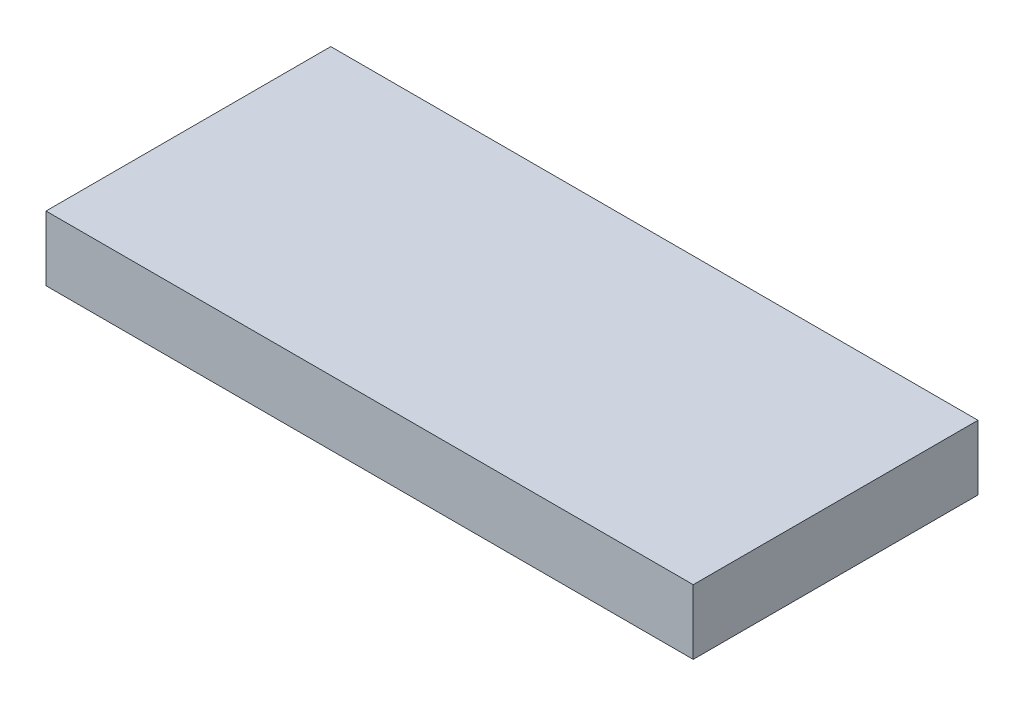
SolidWorks part; units mm, degrees
ref_plane "Front Plane" through (0, 0, 0) normal (0, 0, 1) x (1, 0, 0)
ref_plane "Top Plane" through (0, 0, 0) normal (0, 1, 0) x (1, 0, 0)
ref_plane "Right Plane" through (0, 0, 0) normal (1, 0, 0) x (0, 0, -1)
sketch "Sketch1" plane through (0, 0, 0) normal (0, 1, 0) x (1, 0, 0)
  line L1 (0, 0) -> (50, 0)
  line L2 (0, 0) -> (0, 22)
  line L3 (0, 22) -> (50, 22)
  line L4 (50, 0) -> (50, 22)
  dimension "D1" = 50
  dimension "D2" = 22
extrude "Boss-Extrude1" add sketch "Sketch1" along normal blind 5
